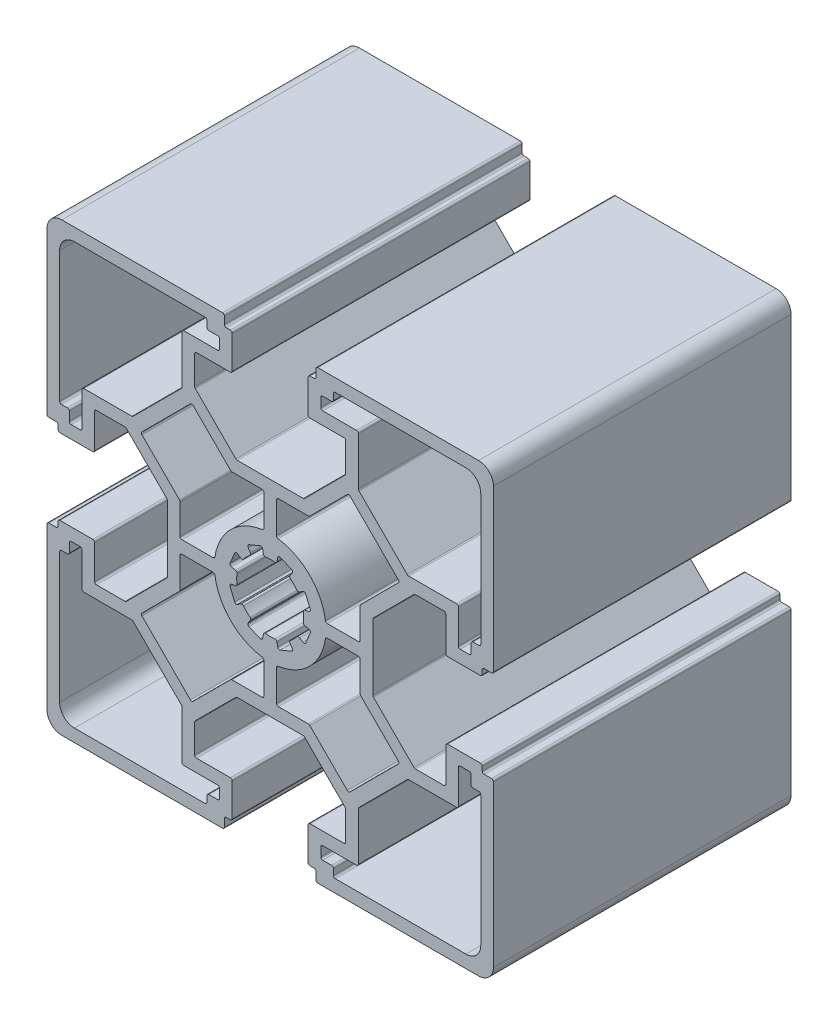
SolidWorks part; units mm, degrees
material "6061 Alaşım"
ref_plane "Ön Düzlem" through (0, 0, 0) normal (0, 0, 1) x (1, 0, 0)
ref_plane "Üst Düzlem" through (0, 0, 0) normal (0, 1, 0) x (1, 0, 0)
ref_plane "Sağ Düzlem" through (0, 0, 0) normal (1, 0, 0) x (0, 0, -1)
sketch "Çizim1" plane through (0, 0, 0) normal (0, 0, 1) x (1, 0, 0)
  line L0 (0, 30) -> (0, -30) construction
  line L1 (-30, -30) -> (30, -30) construction
  line L2 (-30, -30) -> (-30, 30) construction
  line L3 (-30, 30) -> (30, 30) construction
  line L4 (30, -30) -> (30, 30) construction
  line L5 (-30, -30) -> (30, 30) construction
  line L6 (-30, 30) -> (30, -30) construction
  line L7 (-30, 0) -> (30, 0) construction
  point P0 (0, 0)
  dimension "D1" = 60
  dimension "D2" = 60
sketch "Çizim3" plane through (0, 0, 0) normal (0, 0, 1) x (1, 0, 0)
  line L0 (-4.4333, -13.8) -> (4.4333, -13.8)
  line L1 (0, 30) -> (0, -30) construction
  line L2 (4.6101, -13.8732) -> (10.0768, -19.3399)
  line L3 (10.15, -19.5167) -> (10.15, -23.35)
  line L4 (9.9, -23.6) -> (5.35, -23.6)
  line L5 (5.1, -23.85) -> (5.1, -28.25)
  line L6 (5.35, -28.5) -> (5.9, -28.5)
  line L7 (6.15, -28.75) -> (6.15, -29.75)
  line L8 (-30, -30) -> (30, -30) construction
  line L9 (6.4, -30) -> (28, -30)
  line L11 (-30, 30) -> (30, -30) construction
  line L12 (26.3, -28.3) -> (8.75, -28.3)
  line L13 (8.5, -28.05) -> (8.5, -27.25)
  line L14 (8.25, -27) -> (7.05, -27)
  line L15 (6.8, -26.75) -> (6.8, -25.55)
  line L16 (7.05, -25.3) -> (11.6, -25.3)
  line L17 (11.85, -25.05) -> (11.85, -18.6054)
  line L18 (11.9232, -18.4286) -> (18.4286, -11.9232)
  line L20 (17.2265, -10.7211) -> (10.7211, -17.2265)
  line L21 (10.3676, -17.2265) -> (5.3143, -12.1732)
  line L22 (5.1375, -12.1) -> (1.1, -12.1)
  line L23 (0.85, -11.85) -> (0.85, -7.6715)
  line L24 (0, -13.8) -> (0, 0) construction
  line L25 (0, 0) -> (5.3033, -5.3033) construction
  line L26 (1.4311, -7.3622) -> (0, 0) construction
  line L27 (0, 0) -> (4.1939, -6.2178) construction
  line L28 (0.9051, -4.6563) -> (1.0126, -5.2092)
  line L29 (1.3536, -5.3925) -> (2.8559, -4.7702)
  line L30 (2.9675, -4.3994) -> (2.6525, -3.9325)
  line L31 (5.3033, -5.3033) -> (3.182, -3.182) construction
  line L32 (0, -4.5) -> (0, -13.8) construction
  line L33 (-0.9051, -4.6563) -> (-1.0126, -5.2092)
  line L34 (-1.3536, -5.3925) -> (-2.8559, -4.7702)
  line L35 (-2.9675, -4.3994) -> (-2.6525, -3.9325)
  line L36 (-5.3033, -5.3033) -> (-3.182, -3.182) construction
  line L37 (-0.85, -11.85) -> (-0.85, -7.6715)
  line L38 (-5.1375, -12.1) -> (-1.1, -12.1)
  line L39 (-10.3676, -17.2265) -> (-5.3143, -12.1732)
  line L40 (-17.2265, -10.7211) -> (-10.7211, -17.2265)
  line L42 (-11.9232, -18.4286) -> (-18.4286, -11.9232)
  line L43 (-11.85, -25.05) -> (-11.85, -18.6054)
  line L44 (-7.05, -25.3) -> (-11.6, -25.3)
  line L45 (-6.8, -26.75) -> (-6.8, -25.55)
  line L46 (-8.25, -27) -> (-7.05, -27)
  line L47 (-8.5, -28.05) -> (-8.5, -27.25)
  line L48 (-26.3, -28.3) -> (-8.75, -28.3)
  line L50 (-6.4, -30) -> (-28, -30)
  line L51 (-6.15, -28.75) -> (-6.15, -29.75)
  line L52 (-5.35, -28.5) -> (-5.9, -28.5)
  line L53 (-5.1, -23.85) -> (-5.1, -28.25)
  line L54 (-9.9, -23.6) -> (-5.35, -23.6)
  line L55 (-10.15, -19.5167) -> (-10.15, -23.35)
  line L56 (-4.6101, -13.8732) -> (-10.0768, -19.3399)
  line L57 (4.6563, 0.9051) -> (5.2092, 1.0126)
  line L58 (5.3925, 1.3536) -> (4.7702, 2.8559)
  line L59 (4.3994, 2.9675) -> (3.9325, 2.6525)
  line L61 (11.85, 0.85) -> (7.6715, 0.85)
  line L62 (12.1, 5.1375) -> (12.1, 1.1)
  line L63 (17.2265, 10.3676) -> (12.1732, 5.3143)
  line L64 (10.7211, 17.2265) -> (17.2265, 10.7211)
  line L66 (18.4286, 11.9232) -> (11.9232, 18.4286)
  line L67 (25.05, 11.85) -> (18.6054, 11.85)
  line L68 (25.3, 7.05) -> (25.3, 11.6)
  line L69 (26.75, 6.8) -> (25.55, 6.8)
  line L70 (27, 8.25) -> (27, 7.05)
  line L71 (28.05, 8.5) -> (27.25, 8.5)
  line L72 (28.3, 26.3) -> (28.3, 8.75)
  line L74 (30, 6.4) -> (30, 28)
  line L75 (28.75, 6.15) -> (29.75, 6.15)
  line L76 (28.5, 5.35) -> (28.5, 5.9)
  line L77 (23.85, 5.1) -> (28.25, 5.1)
  line L78 (23.6, 9.9) -> (23.6, 5.35)
  line L79 (19.5167, 10.15) -> (23.35, 10.15)
  line L80 (13.8732, 4.6101) -> (19.3399, 10.0768)
  line L81 (13.8, 4.4333) -> (13.8, -4.4333)
  line L82 (13.8732, -4.6101) -> (19.3399, -10.0768)
  line L83 (19.5167, -10.15) -> (23.35, -10.15)
  line L84 (23.6, -9.9) -> (23.6, -5.35)
  line L85 (23.85, -5.1) -> (28.25, -5.1)
  line L86 (28.5, -5.35) -> (28.5, -5.9)
  line L87 (28.75, -6.15) -> (29.75, -6.15)
  line L88 (30, -6.4) -> (30, -28)
  line L89 (28.3, -26.3) -> (28.3, -8.75)
  line L90 (28.05, -8.5) -> (27.25, -8.5)
  line L91 (27, -8.25) -> (27, -7.05)
  line L92 (26.75, -6.8) -> (25.55, -6.8)
  line L93 (25.3, -7.05) -> (25.3, -11.6)
  line L94 (25.05, -11.85) -> (18.6054, -11.85)
  line L95 (17.2265, -10.3676) -> (12.1732, -5.3143)
  line L96 (12.1, -5.1375) -> (12.1, -1.1)
  line L97 (11.85, -0.85) -> (7.6715, -0.85)
  line L98 (4.3994, -2.9675) -> (3.9325, -2.6525)
  line L99 (5.3925, -1.3536) -> (4.7702, -2.8559)
  line L100 (4.6563, -0.9051) -> (5.2092, -1.0126)
  line L101 (-28.3, 26.3) -> (-28.3, 8.75)
  line L102 (-28.05, 8.5) -> (-27.25, 8.5)
  line L103 (-27, 8.25) -> (-27, 7.05)
  line L104 (-26.75, 6.8) -> (-25.55, 6.8)
  line L105 (-25.3, 7.05) -> (-25.3, 11.6)
  line L106 (-25.05, 11.85) -> (-18.6054, 11.85)
  line L107 (-18.4286, 11.9232) -> (-11.9232, 18.4286)
  line L108 (-11.85, 25.05) -> (-11.85, 18.6054)
  line L109 (-7.05, 25.3) -> (-11.6, 25.3)
  line L110 (-6.8, 26.75) -> (-6.8, 25.55)
  line L111 (-8.25, 27) -> (-7.05, 27)
  line L112 (-8.5, 28.05) -> (-8.5, 27.25)
  line L113 (-26.3, 28.3) -> (-8.75, 28.3)
  line L114 (-10.3676, 17.2265) -> (-5.3143, 12.1732)
  line L115 (-5.1375, 12.1) -> (-1.1, 12.1)
  line L116 (-0.85, 11.85) -> (-0.85, 7.6715)
  line L117 (-11.85, 0.85) -> (-7.6715, 0.85)
  line L118 (-12.1, 5.1375) -> (-12.1, 1.1)
  line L119 (-17.2265, 10.3676) -> (-12.1732, 5.3143)
  line L120 (-10.7211, 17.2265) -> (-17.2265, 10.7211)
  line L121 (-30, 6.4) -> (-30, 28)
  line L122 (-28.75, 6.15) -> (-29.75, 6.15)
  line L123 (-28.5, 5.35) -> (-28.5, 5.9)
  line L124 (-23.85, 5.1) -> (-28.25, 5.1)
  line L125 (-23.6, 9.9) -> (-23.6, 5.35)
  line L126 (-19.5167, 10.15) -> (-23.35, 10.15)
  line L127 (-13.8732, 4.6101) -> (-19.3399, 10.0768)
  line L128 (-13.8, -4.4333) -> (-13.8, 4.4333)
  line L129 (-13.8732, -4.6101) -> (-19.3399, -10.0768)
  line L130 (-19.5167, -10.15) -> (-23.35, -10.15)
  line L131 (-23.6, -9.9) -> (-23.6, -5.35)
  line L132 (-23.85, -5.1) -> (-28.25, -5.1)
  line L133 (-28.5, -5.35) -> (-28.5, -5.9)
  line L134 (-28.75, -6.15) -> (-29.75, -6.15)
  line L135 (-30, -6.4) -> (-30, -28)
  line L136 (-28.3, -26.3) -> (-28.3, -8.75)
  line L137 (-28.05, -8.5) -> (-27.25, -8.5)
  line L138 (-27, -8.25) -> (-27, -7.05)
  line L139 (-26.75, -6.8) -> (-25.55, -6.8)
  line L140 (-25.3, -7.05) -> (-25.3, -11.6)
  line L141 (-25.05, -11.85) -> (-18.6054, -11.85)
  line L142 (-17.2265, -10.3676) -> (-12.1732, -5.3143)
  line L143 (-12.1, -5.1375) -> (-12.1, -1.1)
  line L144 (-11.85, -0.85) -> (-7.6715, -0.85)
  line L145 (-4.3994, -2.9675) -> (-3.9325, -2.6525)
  line L146 (-5.3925, -1.3536) -> (-4.7702, -2.8559)
  line L147 (-4.6563, -0.9051) -> (-5.2092, -1.0126)
  line L148 (-4.6563, 0.9051) -> (-5.2092, 1.0126)
  line L149 (-5.3925, 1.3536) -> (-4.7702, 2.8559)
  line L150 (-4.3994, 2.9675) -> (-3.9325, 2.6525)
  line L151 (-2.9675, 4.3994) -> (-2.6525, 3.9325)
  line L152 (-1.3536, 5.3925) -> (-2.8559, 4.7702)
  line L153 (-0.9051, 4.6563) -> (-1.0126, 5.2092)
  line L154 (0.9051, 4.6563) -> (1.0126, 5.2092)
  line L155 (1.3536, 5.3925) -> (2.8559, 4.7702)
  line L156 (2.9675, 4.3994) -> (2.6525, 3.9325)
  line L157 (0.85, 11.85) -> (0.85, 7.6715)
  line L158 (5.1375, 12.1) -> (1.1, 12.1)
  line L159 (10.3676, 17.2265) -> (5.3143, 12.1732)
  line L160 (11.85, 25.05) -> (11.85, 18.6054)
  line L161 (7.05, 25.3) -> (11.6, 25.3)
  line L162 (6.8, 26.75) -> (6.8, 25.55)
  line L163 (8.25, 27) -> (7.05, 27)
  line L164 (8.5, 28.05) -> (8.5, 27.25)
  line L165 (26.3, 28.3) -> (8.75, 28.3)
  line L166 (6.4, 30) -> (28, 30)
  line L167 (6.15, 28.75) -> (6.15, 29.75)
  line L168 (5.35, 28.5) -> (5.9, 28.5)
  line L169 (5.1, 23.85) -> (5.1, 28.25)
  line L170 (9.9, 23.6) -> (5.35, 23.6)
  line L171 (10.15, 19.5167) -> (10.15, 23.35)
  line L172 (4.6101, 13.8732) -> (10.0768, 19.3399)
  line L173 (4.4333, 13.8) -> (-4.4333, 13.8)
  line L174 (-4.6101, 13.8732) -> (-10.0768, 19.3399)
  line L175 (-10.15, 19.5167) -> (-10.15, 23.35)
  line L176 (-9.9, 23.6) -> (-5.35, 23.6)
  line L177 (-5.1, 23.85) -> (-5.1, 28.25)
  line L178 (-5.35, 28.5) -> (-5.9, 28.5)
  line L179 (-6.15, 28.75) -> (-6.15, 29.75)
  line L180 (-6.4, 30) -> (-28, 30)
  circle A0 centre (0, 0) radius 7.5 construction
  arc A1 (1.0645, -7.4241) -> (7.4241, -1.0645) centre (0, 0) ccw
  circle A2 centre (0, 0) radius 4.5 construction
  arc A3 (-0.625, -4.4564) -> (0.625, -4.4564) centre (0, 0) ccw
  arc A4 (2.7092, -3.5931) -> (3.5931, -2.7092) centre (0, 0) ccw
  arc A5 (8.75, -28.3) -> (8.5, -28.05) centre (8.75, -28.05) cw
  arc A6 (8.5, -27.25) -> (8.25, -27) centre (8.25, -27.25) ccw
  arc A7 (7.05, -27) -> (6.8, -26.75) centre (7.05, -26.75) cw
  arc A8 (6.15, -29.75) -> (6.4, -30) centre (6.4, -29.75) ccw
  arc A9 (5.9, -28.5) -> (6.15, -28.75) centre (5.9, -28.75) cw
  arc A10 (5.1, -28.25) -> (5.35, -28.5) centre (5.35, -28.25) ccw
  arc A11 (6.8, -25.55) -> (7.05, -25.3) centre (7.05, -25.55) cw
  arc A12 (5.35, -23.6) -> (5.1, -23.85) centre (5.35, -23.85) ccw
  arc A13 (11.6, -25.3) -> (11.85, -25.05) centre (11.6, -25.05) ccw
  arc A14 (10.15, -23.35) -> (9.9, -23.6) centre (9.9, -23.35) cw
  arc A15 (10.0768, -19.3399) -> (10.15, -19.5167) centre (9.9, -19.5167) cw
  arc A16 (11.85, -18.6054) -> (11.9232, -18.4286) centre (12.1, -18.6054) cw
  arc A17 (10.7211, -17.2265) -> (10.3676, -17.2265) centre (10.5444, -17.0497) cw
  arc A18 (4.4333, -13.8) -> (4.6101, -13.8732) centre (4.4333, -14.05) cw
  arc A19 (5.3143, -12.1732) -> (5.1375, -12.1) centre (5.1375, -12.35) ccw
  arc A20 (1.1, -12.1) -> (0.85, -11.85) centre (1.1, -11.85) cw
  arc A21 (0.85, -7.6715) -> (1.0645, -7.4241) centre (1.1, -7.6715) cw
  arc A22 (2.6525, -3.9325) -> (2.7092, -3.5931) centre (2.8597, -3.7927) cw
  arc A23 (0.9051, -4.6563) -> (0.625, -4.4564) centre (0.6597, -4.704) ccw
  arc A24 (2.8559, -4.7702) -> (2.9675, -4.3994) centre (2.7602, -4.5392) ccw
  arc A25 (1.0126, -5.2092) -> (1.3536, -5.3925) centre (1.258, -5.1615) ccw
  arc A26 (-0.9051, -4.6563) -> (-0.625, -4.4564) centre (-0.6597, -4.704) cw
  arc A27 (-1.0126, -5.2092) -> (-1.3536, -5.3925) centre (-1.258, -5.1615) cw
  arc A28 (-2.8559, -4.7702) -> (-2.9675, -4.3994) centre (-2.7602, -4.5392) cw
  arc A29 (-2.6525, -3.9325) -> (-2.7092, -3.5931) centre (-2.8597, -3.7927) ccw
  arc A30 (-2.7092, -3.5931) -> (-3.5931, -2.7092) centre (0, 0) cw
  arc A31 (-1.0645, -7.4241) -> (-7.4241, -1.0645) centre (0, 0) cw
  arc A32 (-0.85, -7.6715) -> (-1.0645, -7.4241) centre (-1.1, -7.6715) ccw
  arc A33 (-1.1, -12.1) -> (-0.85, -11.85) centre (-1.1, -11.85) ccw
  arc A34 (-5.3143, -12.1732) -> (-5.1375, -12.1) centre (-5.1375, -12.35) cw
  arc A35 (-10.7211, -17.2265) -> (-10.3676, -17.2265) centre (-10.5444, -17.0497) ccw
  arc A36 (-11.85, -18.6054) -> (-11.9232, -18.4286) centre (-12.1, -18.6054) ccw
  arc A37 (-11.6, -25.3) -> (-11.85, -25.05) centre (-11.6, -25.05) cw
  arc A38 (-6.8, -25.55) -> (-7.05, -25.3) centre (-7.05, -25.55) ccw
  arc A39 (-7.05, -27) -> (-6.8, -26.75) centre (-7.05, -26.75) ccw
  arc A40 (-8.5, -27.25) -> (-8.25, -27) centre (-8.25, -27.25) cw
  arc A41 (-8.75, -28.3) -> (-8.5, -28.05) centre (-8.75, -28.05) ccw
  arc A42 (-6.15, -29.75) -> (-6.4, -30) centre (-6.4, -29.75) cw
  arc A43 (-5.9, -28.5) -> (-6.15, -28.75) centre (-5.9, -28.75) ccw
  arc A44 (-5.1, -28.25) -> (-5.35, -28.5) centre (-5.35, -28.25) cw
  arc A45 (-5.35, -23.6) -> (-5.1, -23.85) centre (-5.35, -23.85) cw
  arc A46 (-10.15, -23.35) -> (-9.9, -23.6) centre (-9.9, -23.35) ccw
  arc A47 (-10.0768, -19.3399) -> (-10.15, -19.5167) centre (-9.9, -19.5167) ccw
  arc A48 (-4.4333, -13.8) -> (-4.6101, -13.8732) centre (-4.4333, -14.05) ccw
  arc A49 (4.6563, 0.9051) -> (4.4564, 0.625) centre (4.704, 0.6597) ccw
  arc A50 (5.2092, 1.0126) -> (5.3925, 1.3536) centre (5.1615, 1.258) ccw
  arc A51 (4.7702, 2.8559) -> (4.3994, 2.9675) centre (4.5392, 2.7602) ccw
  arc A52 (3.9325, 2.6525) -> (3.5931, 2.7092) centre (3.7927, 2.8597) cw
  arc A53 (3.5931, 2.7092) -> (2.7092, 3.5931) centre (0, 0) ccw
  arc A54 (7.4241, 1.0645) -> (1.0645, 7.4241) centre (0, 0) ccw
  arc A55 (7.6715, 0.85) -> (7.4241, 1.0645) centre (7.6715, 1.1) cw
  arc A56 (12.1, 1.1) -> (11.85, 0.85) centre (11.85, 1.1) cw
  arc A57 (12.1732, 5.3143) -> (12.1, 5.1375) centre (12.35, 5.1375) ccw
  arc A58 (17.2265, 10.7211) -> (17.2265, 10.3676) centre (17.0497, 10.5444) cw
  arc A59 (18.6054, 11.85) -> (18.4286, 11.9232) centre (18.6054, 12.1) cw
  arc A60 (25.3, 11.6) -> (25.05, 11.85) centre (25.05, 11.6) ccw
  arc A61 (25.55, 6.8) -> (25.3, 7.05) centre (25.55, 7.05) cw
  arc A62 (27, 7.05) -> (26.75, 6.8) centre (26.75, 7.05) cw
  arc A63 (27.25, 8.5) -> (27, 8.25) centre (27.25, 8.25) ccw
  arc A64 (28.3, 8.75) -> (28.05, 8.5) centre (28.05, 8.75) cw
  arc A65 (29.75, 6.15) -> (30, 6.4) centre (29.75, 6.4) ccw
  arc A66 (28.5, 5.9) -> (28.75, 6.15) centre (28.75, 5.9) cw
  arc A67 (28.25, 5.1) -> (28.5, 5.35) centre (28.25, 5.35) ccw
  arc A68 (23.6, 5.35) -> (23.85, 5.1) centre (23.85, 5.35) ccw
  arc A69 (23.35, 10.15) -> (23.6, 9.9) centre (23.35, 9.9) cw
  arc A70 (19.3399, 10.0768) -> (19.5167, 10.15) centre (19.5167, 9.9) cw
  arc A71 (13.8, 4.4333) -> (13.8732, 4.6101) centre (14.05, 4.4333) cw
  arc A72 (13.8, -4.4333) -> (13.8732, -4.6101) centre (14.05, -4.4333) ccw
  arc A73 (19.3399, -10.0768) -> (19.5167, -10.15) centre (19.5167, -9.9) ccw
  arc A74 (23.35, -10.15) -> (23.6, -9.9) centre (23.35, -9.9) ccw
  arc A75 (23.6, -5.35) -> (23.85, -5.1) centre (23.85, -5.35) cw
  arc A76 (28.25, -5.1) -> (28.5, -5.35) centre (28.25, -5.35) cw
  arc A77 (28.5, -5.9) -> (28.75, -6.15) centre (28.75, -5.9) ccw
  arc A78 (29.75, -6.15) -> (30, -6.4) centre (29.75, -6.4) cw
  arc A79 (28.3, -8.75) -> (28.05, -8.5) centre (28.05, -8.75) ccw
  arc A80 (27.25, -8.5) -> (27, -8.25) centre (27.25, -8.25) cw
  arc A81 (27, -7.05) -> (26.75, -6.8) centre (26.75, -7.05) ccw
  arc A82 (25.55, -6.8) -> (25.3, -7.05) centre (25.55, -7.05) ccw
  arc A83 (25.3, -11.6) -> (25.05, -11.85) centre (25.05, -11.6) cw
  arc A84 (18.6054, -11.85) -> (18.4286, -11.9232) centre (18.6054, -12.1) ccw
  arc A85 (17.2265, -10.7211) -> (17.2265, -10.3676) centre (17.0497, -10.5444) ccw
  arc A86 (12.1732, -5.3143) -> (12.1, -5.1375) centre (12.35, -5.1375) cw
  arc A87 (12.1, -1.1) -> (11.85, -0.85) centre (11.85, -1.1) ccw
  arc A88 (7.6715, -0.85) -> (7.4241, -1.0645) centre (7.6715, -1.1) ccw
  arc A89 (3.9325, -2.6525) -> (3.5931, -2.7092) centre (3.7927, -2.8597) ccw
  arc A90 (4.7702, -2.8559) -> (4.3994, -2.9675) centre (4.5392, -2.7602) cw
  arc A91 (5.2092, -1.0126) -> (5.3925, -1.3536) centre (5.1615, -1.258) cw
  arc A92 (4.6563, -0.9051) -> (4.4564, -0.625) centre (4.704, -0.6597) cw
  arc A93 (4.4564, 0.625) -> (4.4564, -0.625) centre (0, 0) cw
  arc A94 (-28.3, 8.75) -> (-28.05, 8.5) centre (-28.05, 8.75) ccw
  arc A95 (-27.25, 8.5) -> (-27, 8.25) centre (-27.25, 8.25) cw
  arc A96 (-27, 7.05) -> (-26.75, 6.8) centre (-26.75, 7.05) ccw
  arc A97 (-25.55, 6.8) -> (-25.3, 7.05) centre (-25.55, 7.05) ccw
  arc A98 (-25.3, 11.6) -> (-25.05, 11.85) centre (-25.05, 11.6) cw
  arc A99 (-18.6054, 11.85) -> (-18.4286, 11.9232) centre (-18.6054, 12.1) ccw
  arc A100 (-11.85, 18.6054) -> (-11.9232, 18.4286) centre (-12.1, 18.6054) cw
  arc A101 (-11.6, 25.3) -> (-11.85, 25.05) centre (-11.6, 25.05) ccw
  arc A102 (-6.8, 25.55) -> (-7.05, 25.3) centre (-7.05, 25.55) cw
  arc A103 (-7.05, 27) -> (-6.8, 26.75) centre (-7.05, 26.75) cw
  arc A104 (-8.5, 27.25) -> (-8.25, 27) centre (-8.25, 27.25) ccw
  arc A105 (-8.75, 28.3) -> (-8.5, 28.05) centre (-8.75, 28.05) cw
  arc A106 (-10.7211, 17.2265) -> (-10.3676, 17.2265) centre (-10.5444, 17.0497) cw
  arc A107 (-5.3143, 12.1732) -> (-5.1375, 12.1) centre (-5.1375, 12.35) ccw
  arc A108 (-1.1, 12.1) -> (-0.85, 11.85) centre (-1.1, 11.85) cw
  arc A109 (-0.85, 7.6715) -> (-1.0645, 7.4241) centre (-1.1, 7.6715) cw
  arc A110 (-7.4241, 1.0645) -> (-1.0645, 7.4241) centre (0, 0) cw
  arc A111 (-7.6715, 0.85) -> (-7.4241, 1.0645) centre (-7.6715, 1.1) ccw
  arc A112 (-12.1, 1.1) -> (-11.85, 0.85) centre (-11.85, 1.1) ccw
  arc A113 (-12.1732, 5.3143) -> (-12.1, 5.1375) centre (-12.35, 5.1375) cw
  arc A114 (-17.2265, 10.7211) -> (-17.2265, 10.3676) centre (-17.0497, 10.5444) ccw
  arc A115 (-29.75, 6.15) -> (-30, 6.4) centre (-29.75, 6.4) cw
  arc A116 (-28.5, 5.9) -> (-28.75, 6.15) centre (-28.75, 5.9) ccw
  arc A117 (-28.25, 5.1) -> (-28.5, 5.35) centre (-28.25, 5.35) cw
  arc A118 (-23.6, 5.35) -> (-23.85, 5.1) centre (-23.85, 5.35) cw
  arc A119 (-23.35, 10.15) -> (-23.6, 9.9) centre (-23.35, 9.9) ccw
  arc A120 (-19.3399, 10.0768) -> (-19.5167, 10.15) centre (-19.5167, 9.9) ccw
  arc A121 (-13.8, 4.4333) -> (-13.8732, 4.6101) centre (-14.05, 4.4333) ccw
  arc A122 (-13.8, -4.4333) -> (-13.8732, -4.6101) centre (-14.05, -4.4333) cw
  arc A123 (-19.3399, -10.0768) -> (-19.5167, -10.15) centre (-19.5167, -9.9) cw
  arc A124 (-23.35, -10.15) -> (-23.6, -9.9) centre (-23.35, -9.9) cw
  arc A125 (-23.6, -5.35) -> (-23.85, -5.1) centre (-23.85, -5.35) ccw
  arc A126 (-28.25, -5.1) -> (-28.5, -5.35) centre (-28.25, -5.35) ccw
  arc A127 (-28.5, -5.9) -> (-28.75, -6.15) centre (-28.75, -5.9) cw
  arc A128 (-29.75, -6.15) -> (-30, -6.4) centre (-29.75, -6.4) ccw
  arc A129 (-28.3, -8.75) -> (-28.05, -8.5) centre (-28.05, -8.75) cw
  arc A130 (-27.25, -8.5) -> (-27, -8.25) centre (-27.25, -8.25) ccw
  arc A131 (-27, -7.05) -> (-26.75, -6.8) centre (-26.75, -7.05) cw
  arc A132 (-25.55, -6.8) -> (-25.3, -7.05) centre (-25.55, -7.05) cw
  arc A133 (-25.3, -11.6) -> (-25.05, -11.85) centre (-25.05, -11.6) ccw
  arc A134 (-18.6054, -11.85) -> (-18.4286, -11.9232) centre (-18.6054, -12.1) cw
  arc A135 (-17.2265, -10.7211) -> (-17.2265, -10.3676) centre (-17.0497, -10.5444) cw
  arc A136 (-12.1732, -5.3143) -> (-12.1, -5.1375) centre (-12.35, -5.1375) ccw
  arc A137 (-12.1, -1.1) -> (-11.85, -0.85) centre (-11.85, -1.1) cw
  arc A138 (-7.6715, -0.85) -> (-7.4241, -1.0645) centre (-7.6715, -1.1) cw
  arc A139 (-3.9325, -2.6525) -> (-3.5931, -2.7092) centre (-3.7927, -2.8597) cw
  arc A140 (-4.7702, -2.8559) -> (-4.3994, -2.9675) centre (-4.5392, -2.7602) ccw
  arc A141 (-5.2092, -1.0126) -> (-5.3925, -1.3536) centre (-5.1615, -1.258) ccw
  arc A142 (-4.6563, -0.9051) -> (-4.4564, -0.625) centre (-4.704, -0.6597) ccw
  arc A143 (-4.4564, -0.625) -> (-4.4564, 0.625) centre (0, 0) cw
  arc A144 (-4.6563, 0.9051) -> (-4.4564, 0.625) centre (-4.704, 0.6597) cw
  arc A145 (-5.2092, 1.0126) -> (-5.3925, 1.3536) centre (-5.1615, 1.258) cw
  arc A146 (-4.7702, 2.8559) -> (-4.3994, 2.9675) centre (-4.5392, 2.7602) cw
  arc A147 (-3.9325, 2.6525) -> (-3.5931, 2.7092) centre (-3.7927, 2.8597) ccw
  arc A148 (-3.5931, 2.7092) -> (-2.7092, 3.5931) centre (0, 0) cw
  arc A149 (-2.6525, 3.9325) -> (-2.7092, 3.5931) centre (-2.8597, 3.7927) cw
  arc A150 (-2.8559, 4.7702) -> (-2.9675, 4.3994) centre (-2.7602, 4.5392) ccw
  arc A151 (-1.0126, 5.2092) -> (-1.3536, 5.3925) centre (-1.258, 5.1615) ccw
  arc A152 (-0.9051, 4.6563) -> (-0.625, 4.4564) centre (-0.6597, 4.704) ccw
  arc A153 (0.625, 4.4564) -> (-0.625, 4.4564) centre (0, 0) ccw
  arc A154 (0.9051, 4.6563) -> (0.625, 4.4564) centre (0.6597, 4.704) cw
  arc A155 (1.0126, 5.2092) -> (1.3536, 5.3925) centre (1.258, 5.1615) cw
  arc A156 (2.8559, 4.7702) -> (2.9675, 4.3994) centre (2.7602, 4.5392) cw
  arc A157 (2.6525, 3.9325) -> (2.7092, 3.5931) centre (2.8597, 3.7927) ccw
  arc A158 (0.85, 7.6715) -> (1.0645, 7.4241) centre (1.1, 7.6715) ccw
  arc A159 (1.1, 12.1) -> (0.85, 11.85) centre (1.1, 11.85) ccw
  arc A160 (5.3143, 12.1732) -> (5.1375, 12.1) centre (5.1375, 12.35) cw
  arc A161 (10.7211, 17.2265) -> (10.3676, 17.2265) centre (10.5444, 17.0497) ccw
  arc A162 (11.85, 18.6054) -> (11.9232, 18.4286) centre (12.1, 18.6054) ccw
  arc A163 (11.6, 25.3) -> (11.85, 25.05) centre (11.6, 25.05) cw
  arc A164 (6.8, 25.55) -> (7.05, 25.3) centre (7.05, 25.55) ccw
  arc A165 (7.05, 27) -> (6.8, 26.75) centre (7.05, 26.75) ccw
  arc A166 (8.5, 27.25) -> (8.25, 27) centre (8.25, 27.25) cw
  arc A167 (8.75, 28.3) -> (8.5, 28.05) centre (8.75, 28.05) ccw
  arc A168 (6.15, 29.75) -> (6.4, 30) centre (6.4, 29.75) cw
  arc A169 (5.9, 28.5) -> (6.15, 28.75) centre (5.9, 28.75) ccw
  arc A170 (5.1, 28.25) -> (5.35, 28.5) centre (5.35, 28.25) cw
  arc A171 (5.35, 23.6) -> (5.1, 23.85) centre (5.35, 23.85) cw
  arc A172 (10.15, 23.35) -> (9.9, 23.6) centre (9.9, 23.35) ccw
  arc A173 (10.0768, 19.3399) -> (10.15, 19.5167) centre (9.9, 19.5167) ccw
  arc A174 (4.4333, 13.8) -> (4.6101, 13.8732) centre (4.4333, 14.05) ccw
  arc A175 (-4.4333, 13.8) -> (-4.6101, 13.8732) centre (-4.4333, 14.05) cw
  arc A176 (-10.0768, 19.3399) -> (-10.15, 19.5167) centre (-9.9, 19.5167) cw
  arc A177 (-10.15, 23.35) -> (-9.9, 23.6) centre (-9.9, 23.35) cw
  arc A178 (-5.35, 23.6) -> (-5.1, 23.85) centre (-5.35, 23.85) ccw
  arc A179 (-5.1, 28.25) -> (-5.35, 28.5) centre (-5.35, 28.25) ccw
  arc A180 (-5.9, 28.5) -> (-6.15, 28.75) centre (-5.9, 28.75) cw
  arc A181 (-6.15, 29.75) -> (-6.4, 30) centre (-6.4, 29.75) ccw
  arc A182 (28.3, -26.3) -> (26.3, -28.3) centre (26.3, -26.3) cw
  arc A183 (-26.3, -28.3) -> (-28.3, -26.3) centre (-26.3, -26.3) cw
  arc A184 (28.3, 26.3) -> (26.3, 28.3) centre (26.3, 26.3) ccw
  arc A185 (-28.3, 26.3) -> (-26.3, 28.3) centre (-26.3, 26.3) cw
  arc A186 (-30, 28) -> (-28, 30) centre (-28, 28) cw
  arc A187 (28, 30) -> (30, 28) centre (28, 28) cw
  arc A188 (28, -30) -> (30, -28) centre (28, -28) ccw
  arc A189 (-30, -28) -> (-28, -30) centre (-28, -28) ccw
  point P45 (8.5, -28.3)
  point P48 (8.5, -27)
  point P51 (6.8, -27)
  point P54 (6.15, -30)
  point P57 (6.15, -28.5)
  point P74 (10.5444, -17.4033)
  point P79 (5.2411, -12.1)
  point P86 (2.5164, -3.7307)
  point P89 (0.8586, -4.4173)
  point P92 (3.1386, -4.6531)
  point P95 (1.0709, -5.5096)
  point P122 (28.3, -28.3)
  point P193 (-28.3, -28.3)
  point P554 (28.3, 28.3)
  point P557 (-28.3, 28.3)
  point P560 (-30, 30)
  point P563 (30, 30)
  point P566 (30, -30)
  point P569 (-30, -30)
  dimension "D1" = 15
  dimension "D22" = 9
  dimension "D24" = 0.25
  dimension "D25" = 2
  dimension "D2" = 0.85
  dimension "D3" = 1.7
  dimension "D4" = 1.7
  dimension "D5" = 1.7
  dimension "D6" = 1.7
  dimension "D7" = 1.7
  dimension "D8" = 1.7
  dimension "D9" = 1.7
  dimension "D10" = 5.1
  dimension "D11" = 6.15
  dimension "D12" = 1.5
  dimension "D13" = 3
  dimension "D14" = 1.7
  dimension "D15" = 1.3
  dimension "D16" = 10.15
  dimension "D17" = 16.2
  dimension "D18" = 4.85
  dimension "D19" = 7.5
  dimension "D20" = 11
  dimension "D21" = 11
  dimension "D23" = 5.5
extrude "Yükseklik-Ekstrüzyon2" add sketch "Çizim3" against normal blind 40
